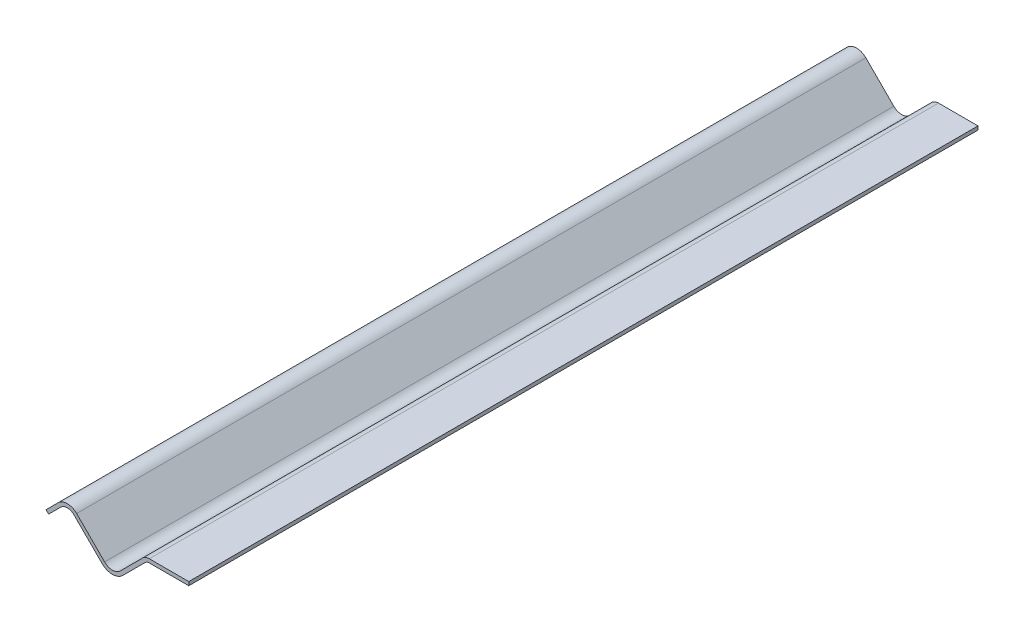
SolidWorks part; units mm, degrees
material "Stainless Steel (ferritic)"
ref_plane "Front Plane" through (0, 0, 0) normal (0, 0, 1) x (1, 0, 0)
ref_plane "Top Plane" through (0, 0, 0) normal (0, 1, 0) x (1, 0, 0)
ref_plane "Right Plane" through (0, 0, 0) normal (1, 0, 0) x (0, 0, -1)
sketch "Sketch2" plane through (0, 0, 0) normal (0, 0, 1) x (1, 0, 0)
  line L0 (0, 0) -> (2.3194, 2.3194)
  line L1 (5.9063, 2.3194) -> (11.2945, -3.0688)
  line L2 (14.3095, -3.0688) -> (18.6118, 1.2336)
  line L3 (19.9023, 1.7681) -> (27.5223, 1.7681)
  line L4 (27.5223, 1.7681) -> (27.5223, 1.0639)
  line L5 (27.5223, 1.0639) -> (19.9023, 1.0639)
  line L6 (19.1098, 0.7356) -> (14.8074, -3.5667)
  line L7 (10.7965, -3.5667) -> (5.4084, 1.8214)
  line L8 (2.8173, 1.8214) -> (0.4979, -0.4979)
  line L9 (0.4979, -0.4979) -> (0, 0)
  arc A0 (2.3194, 2.3194) -> (5.9063, 2.3194) centre (4.1128, 0.5259) cw
  arc A1 (11.2945, -3.0688) -> (14.3095, -3.0688) centre (12.802, -1.5613) ccw
  arc A2 (18.6118, 1.2336) -> (19.9023, 1.7681) centre (19.9023, -0.0569) cw
  arc A3 (19.9023, 1.0639) -> (19.1098, 0.7356) centre (19.9023, -0.0569) ccw
  arc A4 (14.8074, -3.5667) -> (10.7965, -3.5667) centre (12.802, -1.5613) cw
  arc A5 (5.4084, 1.8214) -> (2.8173, 1.8214) centre (4.1128, 0.5259) ccw
  dimension "D1" = 7.62
  dimension "D2" = 6.0844
  dimension "D3" = 7.62
extrude "Boss-Extrude1" add sketch "Sketch2" along normal mid plane 152.146
